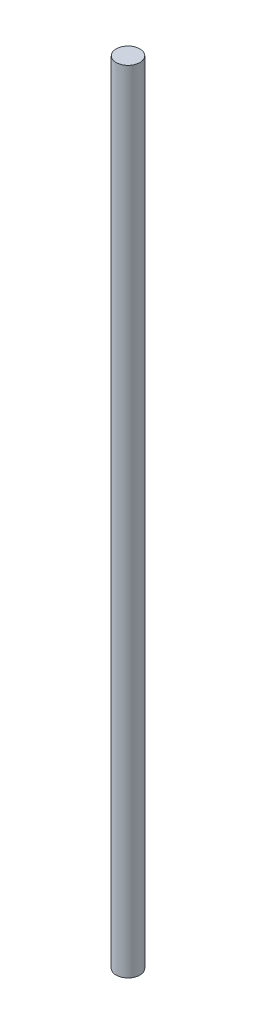
SolidWorks part; units mm, degrees
ref_plane "Front Plane" through (0, 0, 0) normal (0, 0, 1) x (1, 0, 0)
ref_plane "Top Plane" through (0, 0, 0) normal (0, 1, 0) x (1, 0, 0)
ref_plane "Right Plane" through (0, 0, 0) normal (1, 0, 0) x (0, 0, -1)
sketch "Sketch1" plane through (0, 0, 0) normal (0, 1, 0) x (1, 0, 0)
  circle A0 centre (0, 0) radius 3
  point P2 (0, 0)
  dimension "D1" = 6
extrude "Boss-Extrude1" add sketch "Sketch1" along normal blind 200
